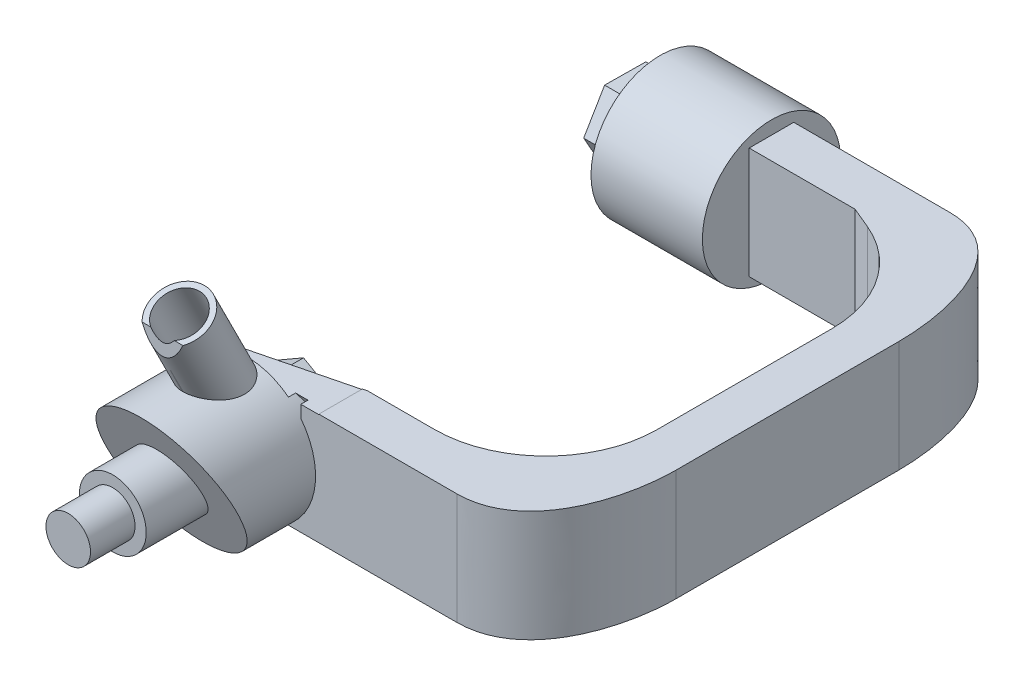
SolidWorks part; units mm, degrees
ref_plane "Front Plane" through (0, 0, 0) normal (0, 0, 1) x (1, 0, 0)
ref_plane "Top Plane" through (0, 0, 0) normal (0, 1, 0) x (1, 0, 0)
ref_plane "Right Plane" through (0, 0, 0) normal (1, 0, 0) x (0, 0, -1)
sketch "Sketch1" plane through (0, 0, 0) normal (0, 1, 0) x (1, 0, 0)
  line L0 (0, 0) -> (76.2, 0)
  line L1 (76.2, 0) -> (101.6, 0)
  line L2 (228.6, 127) -> (228.6, 326.1152)
  line L3 (3.1176, 457.1894) -> (123.7407, 457.1894)
  line L4 (123.7407, 457.1894) -> (147.939, 447.1067)
  line L5 (0, 0) -> (0, -50.8)
  line L6 (0, -50.8) -> (127, -50.8)
  line L7 (127, -50.8) -> (177.8, -50.8)
  line L8 (3.1176, 457.1894) -> (3.1176, 507.9894)
  line L9 (3.1176, 507.9894) -> (130.1176, 507.9894)
  line L10 (130.1176, 507.9894) -> (180.9176, 507.9894)
  line L11 (279.4, 351.5152) -> (279.4, 97.5152)
  arc A0 (101.6, 0) -> (228.6, 127) centre (101.6, 127) ccw
  arc A1 (147.939, 447.1067) -> (228.6, 326.1152) centre (97.5259, 326.1152) cw
  spline S0 degree 3 poles (180.9176, 507.9894) (258.0968, 507.9894) (279.4, 408.3661) (279.4, 351.5152) knots 0 0 0 0 0.284384 0.284384 0.284384 0.284384
  spline S1 degree 3 poles (279.4, 97.5152) (279.4, 39.9495) (253.6127, -50.8) (177.8, -50.8) knots 0.713424 0.713424 0.713424 0.713424 1 1 1 1
  dimension "D1" = 50.8
  dimension "D4" = 127
  dimension "D7" = 50.8
  dimension "D9" = 50.8
  dimension "D10" = 25.4
  dimension "D2" = 457.2
  dimension "D3" = 50.8
  dimension "D5" = 127
  dimension "D6" = 50.8
  dimension "D8" = 254
extrude "Boss-Extrude1" add sketch "Sketch1" along normal blind 127
sketch "Sketch2" plane through (3.1176, 0, 0) normal (-1, 0, 0) x (0, 0, 1)
  circle A0 centre (-482.5894, 63.5) radius 78.74
  dimension "D1" = 157.48
extrude "Boss-Extrude2" add sketch "Sketch2" along normal blind 127
sketch "Sketch3" plane through (-123.8824, 0, 0) normal (-1, 0, 0) x (0, 0, 1)
  line L1 (-435.6647, 63.9705) -> (-459.5345, 104.3732)
  line L2 (-459.5345, 104.3732) -> (-506.4592, 103.9027)
  line L3 (-506.4592, 103.9027) -> (-529.514, 63.0295)
  line L4 (-529.514, 63.0295) -> (-505.6442, 22.6268)
  line L5 (-505.6442, 22.6268) -> (-458.7195, 23.0973)
  line L6 (-458.7195, 23.0973) -> (-435.6647, 63.9705)
  circle A0 centre (-482.5894, 63.5) radius 40.64 construction
  dimension "D1" = 81.28
extrude "Boss-Extrude3" add sketch "Sketch3" along normal blind 40.132
sketch "Sketch4" plane through (0, 0, 0) normal (-1, 0, 0) x (0, 0, 1)
  line L1 (50.8, 127) -> (0, 127)
  line L2 (50.8, 127) -> (50.8, 0)
  line L3 (50.8, 0) -> (0, 0)
  line L4 (0, 127) -> (0, 0)
extrude "Boss-Extrude4" add sketch "Sketch4" along normal blind 127
sketch "Sketch5" plane through (0, 0, 0) normal (0, -1, 0) x (-1, 0, 0)
  line L0 (127, -38.1) -> (127, 0)
  line L2 (127, 0) -> (127, -50.8) construction
  line L3 (127, 0) -> (-25.4, 0)
  line L4 (-101.6, 0) -> (127, 0) construction
  line L5 (-25.4, 0) -> (127, -38.1)
  dimension "D1" = 38.1
  dimension "D2" = 152.4
extrude "Cut-Extrude1" cut sketch "Sketch5" against normal through all
sketch "Sketch7" plane through (0, 0, 50.8) normal (0, 0, 1) x (1, 0, 0)
  line L0 (-127, 0) -> (-127, 127) construction
  line L1 (-60.3824, 110.427) -> (-101.0224, 86.9635)
  line L2 (-101.0224, 86.9635) -> (-101.0224, 40.0365)
  line L3 (-101.0224, 40.0365) -> (-60.3824, 16.573)
  line L4 (-60.3824, 16.573) -> (-19.7424, 40.0365)
  line L5 (-19.7424, 40.0365) -> (-19.7424, 86.9635)
  line L6 (-19.7424, 86.9635) -> (-60.3824, 110.427)
  circle A0 centre (-60.3824, 63.5) radius 40.64 construction
  point P11 (-127, 63.5)
  dimension "D1" = 81.28
  dimension "D2" = 0
extrude "Boss-Extrude6" add sketch "Sketch7" against normal blind 63.5
sketch "Sketch9" plane through (0, 0, 50.8) normal (0, 0, 1) x (1, 0, 0)
  line L0 (-127, 0) -> (-127, 127) construction
  line L1 (-61.9412, 110.427) -> (-102.5812, 86.9635)
  line L2 (-102.5812, 86.9635) -> (-102.5812, 40.0365)
  line L3 (-102.5812, 40.0365) -> (-61.9412, 16.573)
  line L4 (-61.9412, 16.573) -> (-21.3012, 40.0365)
  line L5 (-21.3012, 40.0365) -> (-21.3012, 86.9635)
  line L6 (-21.3012, 86.9635) -> (-61.9412, 110.427)
  circle A0 centre (-61.9412, 63.5) radius 40.64 construction
  point P10 (-127, 63.5)
  dimension "D1" = 81.28
  dimension "D2" = 0
extrude "Boss-Extrude7" add sketch "Sketch9" along normal blind 0.254
sketch "Sketch10" plane through (0, 0, 50.8) normal (0, 0, 1) x (1, 0, 0)
  circle A0 centre (-61.9412, 63.9705) radius 78.74
  dimension "D1" = 157.48
extrude "Boss-Extrude8" add sketch "Sketch10" along normal blind 127
ref_plane "Plane1" through (-139.7, 0, 0) normal (1, 0, 0) x (0, 0, -1)
sketch "Sketch11" plane through (-139.7, 0, 0) normal (1, 0, 0) x (0, 0, -1)
  line L0 (-99.5457, -18.2304) -> (-194.9831, 195.6189)
  line L1 (-99.5457, -18.2304) -> (-201.1457, -18.2304)
  line L2 (-201.1457, -18.2304) -> (-201.1457, 206.9054)
  line L3 (-201.1457, 206.9054) -> (-194.9831, 195.6189)
  dimension "D1" = 101.6
extrude "Cut-Extrude4" cut sketch "Sketch11" along normal mid plane 2540
sketch "Sketch12" plane through (0, 0, 50.8) normal (0, 0, 1) x (1, 0, 0)
  circle A0 centre (-61.9412, 63.9705) radius 38.1
  dimension "D1" = 76.2
extrude "Boss-Extrude9" add sketch "Sketch12" along normal blind 152.4
sketch "Sketch13" plane through (0, 0, 203.2) normal (0, 0, 1) x (1, 0, 0)
  circle A0 centre (-61.9412, 63.9705) radius 25.4
  dimension "D1" = 50.8
extrude "Boss-Extrude10" add sketch "Sketch13" along normal blind 50.8
sketch "Sketch18" plane through (0, 0, 0) normal (1, 0, 0) x (0, 0, -1)
  line L7 (-97.2949, 235.3672) -> (-50.8, 142.7105)
  line L13 (-136.693, 172.2976) -> (-154.0502, 206.8876)
  line L14 (-154.0502, 206.8876) -> (-97.2949, 235.3672)
  line L15 (-50.8, 142.7105) -> (-106.8051, 112.7827)
  line L16 (-106.8051, 112.7827) -> (-136.693, 172.2976)
  dimension "D2" = 63.5
  dimension "D1" = 63.5
extrude "Boss-Extrude11" add sketch "Sketch18" against normal blind 127
sketch "Sketch21" plane through (0, 227.0246, 113.9204) normal (0, 0.8938, 0.4485) x (1, 0, 0)
  line L14 (0, -44.8987) -> (0, 18.6013)
  line L15 (-127, -44.8987) -> (0, -44.8987)
  line L16 (0, 18.6013) -> (-127, 18.6013)
  line L17 (-127, 18.6013) -> (-127, -44.8987)
  line L18 (0, -44.8987) -> (0, 18.6013)
  line L19 (-127, -44.8987) -> (0, -44.8987)
  line L20 (0, 18.6013) -> (-127, 18.6013)
  line L21 (-127, 18.6013) -> (-127, -44.8987)
  circle A0 centre (-63.5, -13.1487) radius 31.75
  line M2 (0, -44.8987) -> (0, 18.6013)
  line M3 (0, 18.6013) -> (-127, 18.6013)
  line M4 (-127, 18.6013) -> (-127, -44.8987)
  line M5 (-127, -44.8987) -> (0, -44.8987)
  dimension "D1" = 0
extrude "Cut-Extrude11" cut sketch "Sketch21" against normal up to surface and the other way through all contours A0 L19 M2 M3 | A0 L20 M4 M5 up to face at (-73.2658, 92.9484, 60.8511)
sketch "Sketch22" plane through (0, 227.0246, 113.9204) normal (0, 0.8938, 0.4485) x (1, 0, 0)
  circle A0 centre (-63.5, -13.1487) radius 25.4
  dimension "D1" = 50.8
extrude "Cut-Extrude12" cut sketch "Sketch22" against normal blind 76.2
sketch "Sketch23" plane through (0, 0, 0) normal (1, 0, 0) x (0, 0, -1)
  line L0 (-154.0502, 206.8876) -> (-145.3716, 189.5926)
  line L1 (-154.0502, 206.8876) -> (-136.693, 172.2976) construction
  line L3 (-102.9704, 232.5193) -> (-148.3746, 209.7355) construction
  line L4 (-144.9693, 211.4443) -> (-154.0502, 206.8876)
  line L5 (-145.3716, 189.5926) -> (-144.9693, 211.4443)
  dimension "D1" = 10.16
extrude "Cut-Extrude13" cut sketch "Sketch23" against normal through all
sketch "Sketch24" plane through (0, 127, 0) normal (0, 1, 0) x (1, 0, 0)
  line L0 (20.493, -50.8) -> (20.493, -1.2267)
  line L1 (0, -50.8) -> (177.8, -50.8) construction
  line L2 (-127, -38.1) -> (25.4, 0) construction
  line L3 (20.493, -1.2267) -> (-127, -38.1)
  line L4 (-127, -38.1) -> (-127, -50.8)
  line L5 (-127, -50.8) -> (20.493, -50.8)
extrude "Cut-Extrude16" cut sketch "Sketch24" against normal blind 0.508
